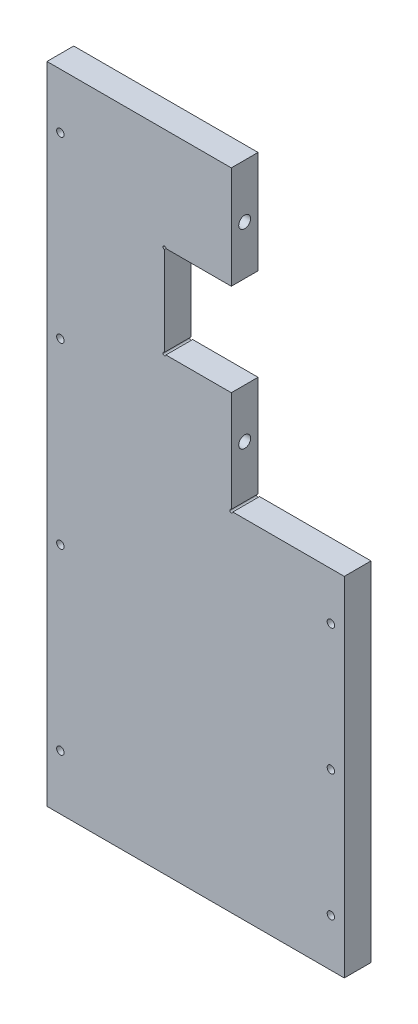
SolidWorks part; units mm, degrees
ref_plane "Front Plane" through (0, 0, 0) normal (0, 0, 1) x (1, 0, 0)
ref_plane "Top Plane" through (0, 0, 0) normal (0, 1, 0) x (1, 0, 0)
ref_plane "Right Plane" through (0, 0, 0) normal (1, 0, 0) x (0, 0, -1)
sketch "Sketch1" plane through (0, 0, 0) normal (0, 0, 1) x (1, 0, 0)
  line L0 (200, 234) -> (124, 234)
  line L1 (0, 0) -> (200, 0)
  line L2 (0, 0) -> (0, 434)
  line L3 (124, 434) -> (124, 365)
  line L4 (200, 0) -> (200, 234)
  line L5 (124, 434) -> (0, 434)
  line L6 (124, 365) -> (79, 365)
  line L7 (79, 365) -> (79, 303)
  line L8 (79, 303) -> (124, 303)
  line L9 (124, 303) -> (124, 234)
  dimension "D1" = 200
  dimension "D2" = 234
  dimension "D3" = 124
  dimension "D4" = 434
  dimension "D5" = 69
  dimension "D6" = 69
  dimension "D7" = 45
  dimension "D8" = 124
extrude "Boss-Extrude1" add sketch "Sketch1" along normal blind 18
sketch "Sketch2" plane through (0, 0, 18) normal (0, 0, 1) x (1, 0, 0)
  circle A0 centre (79, 365) radius 1
  circle A1 centre (79, 303) radius 1
  circle A2 centre (124, 234) radius 1
  dimension "D1" = 2
  dimension "D2" = 2
  dimension "D3" = 2
extrude "Cut-Extrude1" cut sketch "Sketch2" against normal blind 18
hole_wizard "Ø5.0 (5) Diameter Hole1" positions "Sketch4" profile "Sketch3" hole size "Ø5.0" standard "ISO" end condition through all
sketch "Sketch4" plane through (0, 0, 18) normal (0, 0, 1) x (1, 0, 0)
  line L0 (0, 434) -> (0, 0) construction
  line L1 (0, 0) -> (200, 0) construction
  point P0 (9, 397)
  point P2 (9, 277)
  point P4 (9, 157)
  point P6 (9, 37)
  dimension "D1" = 9
  dimension "D2" = 9
  dimension "D3" = 9
  dimension "D4" = 9
  dimension "D5" = 120
  dimension "D6" = 120
  dimension "D7" = 120
  dimension "D8" = 37
sketch "Sketch3" plane through (9, 397, 18) normal (1, 0, 0) x (0, -1, 0)
  line L0 (0, 0) -> (0, 18)
  line L1 (0, 18) -> (2.5, 18)
  line L2 (2.5, 18) -> (2.5, 0)
  line L5 (2.5, 0) -> (0, 0)
  line L11 (0, -6.35) -> (0, 107.95) construction
  dimension "Thru Hole Dia." = 5
  dimension "Thru Hole Depth" = 18
hole_wizard "Ø5.0 (5) Diameter Hole2" positions "Sketch6" profile "Sketch5" hole size "Ø5.0" standard "ISO" end condition through all
sketch "Sketch6" plane through (0, 0, 0) normal (0, 0, -1) x (-1, 0, 0)
  line L0 (-200, 0) -> (-200, 234) construction
  line L1 (-200, 234) -> (-125, 234) construction
  point P0 (-191, 202)
  point P2 (-191, 117)
  point P4 (-191, 32)
  dimension "D1" = 9
  dimension "D2" = 9
  dimension "D3" = 9
  dimension "D4" = 85
  dimension "D5" = 85
  dimension "D6" = 32
sketch "Sketch5" plane through (191, 202, 0) normal (1, 0, 0) x (0, 1, 0)
  line L0 (0, 0) -> (0, 18)
  line L1 (0, 18) -> (2.5, 18)
  line L2 (2.5, 18) -> (2.5, 0)
  line L5 (2.5, 0) -> (0, 0)
  line L11 (0, -6.35) -> (0, 107.95) construction
  dimension "Thru Hole Dia." = 5
  dimension "Thru Hole Depth" = 18
hole_wizard "Ø8.0 (8) Diameter Hole1" positions "Sketch8" profile "Sketch7" hole size "Ø8.0" standard "ISO"
sketch "Sketch8" plane through (124, 0, 0) normal (1, 0, 0) x (0, 0, -1)
  point P0 (-9, 398)
  point P3 (-9, 270)
sketch "Sketch7" plane through (124, 398, 9) normal (0, 1, 0) x (0, 0, -1)
  line L0 (0, 0) -> (0, 26)
  line L1 (0, 26) -> (4, 26)
  line L2 (4, 26) -> (4, 0)
  line L5 (4, 0) -> (0, 0)
  line L10 (0, 26) -> (-4, 26) construction
  line L11 (0, -6.35) -> (0, 107.95) construction
  dimension "Hole Dia." = 8
  dimension "Hole Depth" = 26
  dimension "Drill Angle" = 180
